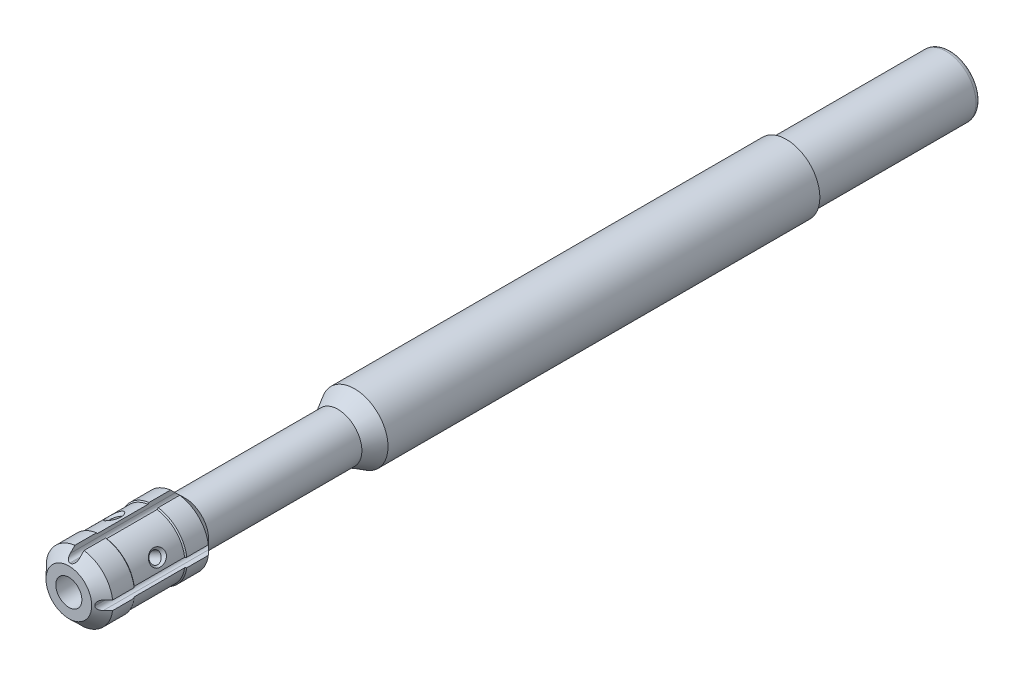
SolidWorks part; units mm, degrees
ref_plane "Front Plane" through (0, 0, 0) normal (0, 0, 1) x (1, 0, 0)
ref_plane "Top Plane" through (0, 0, 0) normal (0, 1, 0) x (1, 0, 0)
ref_plane "Right Plane" through (0, 0, 0) normal (1, 0, 0) x (0, 0, -1)
ref_axis "Axis1" through (0, 0, -4.7492) along (0, 0, 1)
sketch "Sketch5" plane through (0, 0, 0) normal (1, 0, 0) x (0, 0, -1)
  line L0 (-72.6694, 3.4417) -> (-67.31, 3.4417)
  line L1 (-47.6195, 2.54) -> (-45.8597, 3.556)
  line L2 (-63.8937, 2.54) -> (-64.9097, 3.556)
  line L3 (17.4752, 0) -> (-67.4506, 0)
  line L4 (-76.2, 1.3843) -> (-76.2, 2.4257)
  line L5 (-75.0697, 3.556) -> (-76.2, 2.4257)
  line L6 (-63.8937, 2.54) -> (-47.6195, 2.54)
  line L7 (31.3644, 0) -> (17.4752, 0) construction
  line L8 (0, 3.175) -> (17.4752, 3.175)
  line L9 (17.4752, 3.175) -> (17.4752, 0)
  line L10 (-67.4506, 0) -> (-68.2498, 1.3843)
  line L11 (-68.2498, 1.3843) -> (-76.2, 1.3843)
  line L12 (-67.1957, 3.556) -> (-64.9097, 3.556)
  line L13 (-67.1957, 3.556) -> (-67.31, 3.4417)
  line L14 (-72.6694, 3.4417) -> (-72.7837, 3.556)
  line L15 (-72.7837, 3.556) -> (-75.0697, 3.556)
  line L16 (0, 3.175) -> (0, 3.556)
  line L17 (0, 3.556) -> (-45.8597, 3.556)
  point P2 (-69.9897, 3.4417)
  point P3 (-69.85, 0)
  dimension "D1" = 5.08
  dimension "D2" = 7.112
  dimension "D3" = 69.85
  dimension "D4" = 30
  dimension "D5" = 17.4752
  dimension "D6" = 5.588
  dimension "D7" = 6.35
  dimension "D8" = 6.35
  dimension "D9" = 6.8834
  dimension "D10" = 45
  dimension "D11" = 45
  dimension "D12" = 2.7686
  dimension "D13" = 60
  dimension "D14" = 7.9502
  dimension "D15" = 1.1303
  dimension "D16" = 5.08
  dimension "D17" = 5.08
  dimension "D18" = 19.05
  dimension "D19" = 0.1143
  dimension "D20" = 7.112
  dimension "D21" = 1.016
revolve "Revolve1" add sketch "Sketch5" angle 360 about L7
sketch "Sketch13" plane through (0, 0, 76.2) normal (0, 0, 1) x (1, 0, 0)
  line L0 (0.4826, 3.9921) -> (0.4826, 3.0226)
  line L1 (-0.4826, 3.0226) -> (-0.4826, 3.9921)
  line L2 (-0.4826, 3.9921) -> (0.4826, 3.9921)
  line L3 (0.0508, 2.5908) -> (-0.0508, 2.5908)
  arc A0 (0.4826, 3.0226) -> (0.0508, 2.5908) centre (0.0508, 3.0226) cw
  circle A1 centre (0, 3.0391) radius 0.4483 construction
  arc A2 (-0.0508, 2.5908) -> (-0.4826, 3.0226) centre (-0.0508, 3.0226) cw
  circle A4 centre (0, 0) radius 3.4417 construction
  point P8 (0, 3.9921)
  dimension "D1" = 0.9652
  dimension "D2" = 0.8966
  dimension "D5" = 0.4318
  dimension "D3" = 0.0457
  dimension "D4" = 2.5908
  dimension "D6" = 3.0391
extrude "Cut-Extrude2" cut sketch "Sketch13" against normal up to next
pattern_circular "CirPattern1" count 4 over 360 about axis through (0, 0, 0) along (0, 0, 1) of "Cut-Extrude2"
ref_plane "Plane1" through (0, 0, 69.85) normal (0, 0, 1) x (1, 0, 0)
sketch "Sketch14" plane through (0, 0, 69.85) normal (0, 0, 1) x (1, 0, 0)
  line L0 (3.7128, 1.8918) -> (-3.7128, -1.8918)
  line L1 (3.0785, 0.8987) -> (-2.5366, -1.9624)
  line L2 (3.0785, 0.8987) -> (4.445, 0.4547)
  line L3 (-3.7128, -1.8918) -> (-2.9806, -3.3289)
  line L4 (4.445, 0.4547) -> (3.7128, 1.8918)
  line L5 (3.7128, 1.8918) -> (4.2888, 2.1853) construction
  line L6 (-2.9806, -3.3289) -> (-2.5366, -1.9624)
  line L7 (0.271, -0.5318) -> (3.3728, -0.5318) construction
  line L8 (0, 0) -> (0.271, -0.5318) construction
  circle A0 centre (0, 0) radius 3.556 construction
  point P9 (3.4714, 0.771)
  dimension "D1" = 27
  dimension "D2" = 45
  dimension "D3" = 1.1938
  dimension "D4" = 3.151
  dimension "D5" = 1.016
  dimension "D6" = 1.778
revolve "Cut-Revolve1" cut sketch "Sketch14" angle 360 about L5
pattern_circular "CirPattern2" count 2 over 90 about axis through (0, 0, -4.7492) along (0, 0, 1) of "Cut-Revolve1"
fillet "Fillet1" radius 0.508 1 edges at (0, 3.175, -17.4752)
sketch "Sketch15" [suppressed] plane through (0, 0, 0) normal (0, 1, 0) x (1, 0, 0)
  line L0 (2.3928, -76.2) -> (3.5231, -75.0697)
  line L1 (3.5231, -75.0697) -> (3.5231, -66.8788)
  line L2 (3.5231, -72.7837) -> (3.5231, -75.0697) construction
  line L3 (-2.4257, -76.2) -> (2.4257, -76.2) construction
  line L4 (2.3928, -76.2) -> (2.0118, -76.581)
  line L5 (0, -71.922) -> (0, -80.736) construction
  dimension "D1" = 45
  dimension "D2" = 0.381
sketch "Sketch16" plane through (0, 0, 76.2) normal (0, 0, 1) x (1, 0, 0)
  line L0 (-0.0508, -2.5908) -> (0.0508, -2.5908) construction
  line L1 (-0.4385, -3.4798) -> (0.4725, -3.4798)
  line L2 (0.0508, 2.5908) -> (-0.0508, 2.5908) construction
  line L3 (0.4274, 3.4798) -> (-0.4385, 3.4798)
  circle A0 centre (0, -3.0353) radius 0.4445
  circle A1 centre (0, 3.0353) radius 0.4445
  dimension "D1" = 0.889
  dimension "D2" = 0.889
